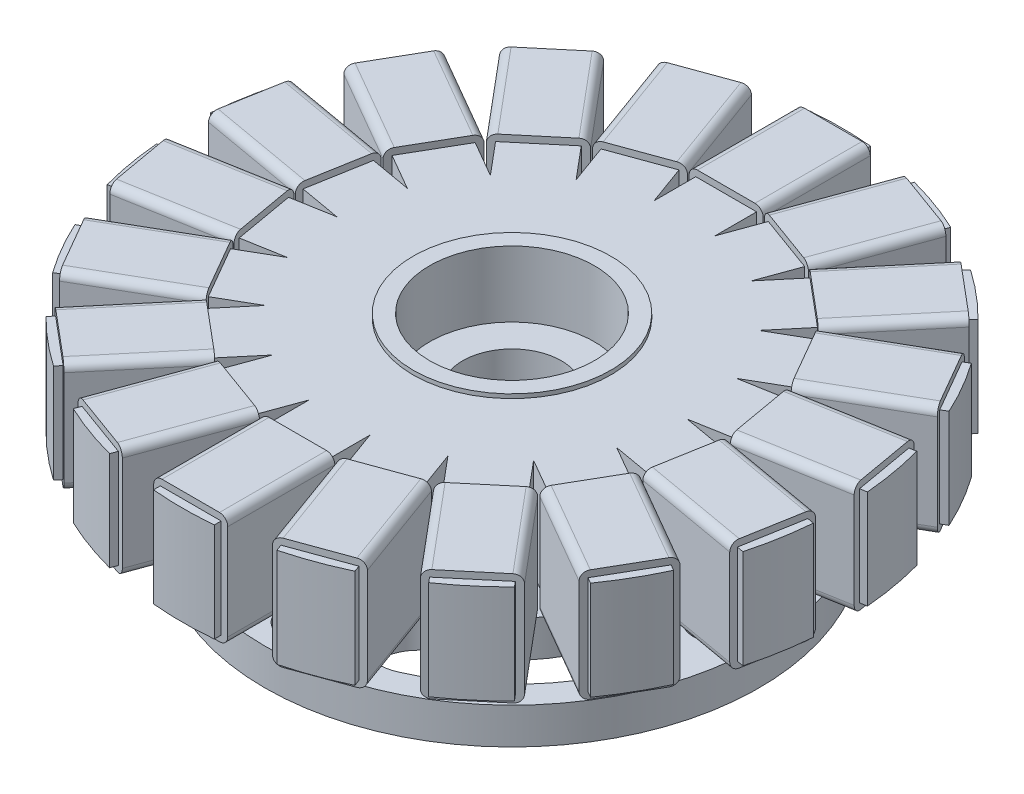
SolidWorks part; units mm, degrees
material "Stainless Steel (ferritic)"
ref_plane "Front Plane" through (0, 0, 0) normal (0, 0, 1) x (1, 0, 0)
ref_plane "Top Plane" through (0, 0, 0) normal (0, 1, 0) x (1, 0, 0)
ref_plane "Right Plane" through (0, 0, 0) normal (1, 0, 0) x (0, 0, -1)
sketch "Sketch1" plane through (0, 0, 0) normal (0, 1, 0) x (1, 0, 0)
  circle A0 centre (0, 0) radius 15
  circle A1 centre (0, 0) radius 12.5 construction
  circle A2 centre (0, 12.5) radius 1.5
  circle A3 centre (12.5, 0) radius 1.5
  circle A4 centre (0, -12.5) radius 1.5
  circle A5 centre (-12.5, 0) radius 1.5
  point P15 (0, 0)
  dimension "D1" = 30
  dimension "D2" = 25
  dimension "D3" = 3
  dimension "D4" = 4
extrude "Boss-Extrude1" add sketch "Sketch1" along normal blind 2.2
sketch "Sketch2" plane through (0, 2.2, 0) normal (0, 1, 0) x (1, 0, 0)
  circle A0 centre (0, 0) radius 6
  dimension "D1" = 12
extrude "Boss-Extrude2" add sketch "Sketch2" along normal blind 10
sketch "Sketch3" plane through (0, 0, 0) normal (0, -1, 0) x (1, 0, 0)
  circle A0 centre (0, 0) radius 5
  dimension "D1" = 10
extrude "Cut-Extrude1" cut sketch "Sketch3" against normal blind 4 contours A0
sketch "Sketch4" plane through (0, 12.2, 0) normal (0, 1, 0) x (1, 0, 0)
  circle A0 centre (0, 0) radius 5
  dimension "D1" = 10
extrude "Cut-Extrude2" cut sketch "Sketch4" against normal blind 4
sketch "Sketch5" plane through (0, 8.2, 0) normal (0, 1, 0) x (1, 0, 0)
  circle A0 centre (0, 0) radius 3
  dimension "D1" = 6
extrude "Cut-Extrude3" cut sketch "Sketch5" against normal blind 10
sketch "Sketch6" plane through (0, 0, 0) normal (0, -1, 0) x (1, 0, 0)
  line L0 (-4.4173, 10.0741) -> (-10.0741, 4.4173) construction
  line L1 (-10.0741, 4.4173) -> (-5.6195, 4.4173) construction
  circle A0 centre (0, 0) radius 11 construction
  arc A1 (-4.4173, 10.0741) -> (-10.0741, 4.4173) centre (0, 0) ccw construction
  arc A2 (-5.4008, 12.3172) -> (-12.3172, 5.4008) centre (0, 0) ccw
  arc A3 (-3.4337, 7.831) -> (-7.831, 3.4337) centre (0, 0) ccw
  arc A4 (-3.4337, 7.831) -> (-5.4008, 12.3172) centre (-4.4173, 10.0741) ccw
  arc A5 (-12.3172, 5.4008) -> (-7.831, 3.4337) centre (-10.0741, 4.4173) ccw
  point P7 (-7.7782, 7.7782)
  dimension "D3" = 22
  dimension "D1" = 45
  dimension "D2" = 8
extrude "Cut-Extrude4" cut sketch "Sketch6" against normal blind 2.2
pattern_circular "CirPattern1" count 4 over 360 about axis through (0, 0, 0) along (0, 1, 0) of "Cut-Extrude4"
ref_plane "Plane1" through (0, 11.95, 0) normal (0, 1, 0) x (1, 0, 0)
sketch "Sketch7" plane through (0, 11.95, 0) normal (0, 1, 0) x (1, 0, 0)
  line L2 (0, 0) -> (-19.6962, -3.473) construction
  line L3 (-19.2915, -5.2763) -> (-9.991, -3.6364)
  line L4 (-19.9327, -1.6399) -> (-10.6322, 0)
  line L5 (-10.6322, 0) -> (-20, 0) construction
  line L6 (-9.991, -3.6364) -> (-18.7939, -6.8404) construction
  line L7 (-6, 0) -> (-10.6322, 0)
  line L8 (-5.6382, -2.0521) -> (-9.991, -3.6364)
  circle A0 centre (0, 0) radius 20 construction
  arc A1 (-19.9327, -1.6399) -> (-19.2915, -5.2763) centre (0, 0) ccw
  circle A2 centre (0, 0) radius 6 construction
  circle A3 centre (0, 0) radius 6
  arc A4 (-6, 0) -> (-5.6382, -2.0521) centre (0, 0) ccw
  dimension "D1" = 40
extrude "Boss-Extrude3" add sketch "Sketch7" against normal blind 6 contours L4 L7 A4 L8 L3 A1
pattern_circular "CirPattern2" count 18 over 360 about axis through (0, 0, 0) along (0, 1, 0) of "Boss-Extrude3"
ref_plane "Plane2" through (0, 0, 13) normal (0, 0, 1) x (1, 0, 0)
sketch "Sketch9" plane through (0, 0, 13) normal (0, 0, 1) x (1, 0, 0)
  line L0 (1.8463, 5.95) -> (1.8463, 11.95) construction
  line L1 (-1.8463, 5.95) -> (1.8463, 5.95) construction
  line L2 (-1.8463, 5.95) -> (-1.8463, 11.95) construction
  line L3 (1.8463, 11.95) -> (-1.8463, 11.95) construction
  line L4 (1.8463, 5.95) -> (1.8463, 11.95)
  line L5 (-1.8463, 5.95) -> (1.8463, 5.95)
  line L6 (-1.8463, 5.95) -> (-1.8463, 11.95)
  line L7 (1.8463, 11.95) -> (-1.8463, 11.95)
  line L9 (-2.2463, 12.35) -> (2.2463, 12.35)
  line L10 (-2.2463, 12.35) -> (-2.2463, 5.55)
  line L11 (-2.2463, 5.55) -> (2.2463, 5.55)
  line L12 (2.2463, 12.35) -> (2.2463, 5.55)
  dimension "D1" = 0.4
  dimension "D2" = 0.4
  dimension "D3" = 0.4
  dimension "D4" = 0.4
extrude "Boss-Extrude4" add sketch "Sketch9" along normal blind 6.5
fillet "Fillet1" radius 0.5 4 edges at (2.2463, 5.55, 16.25) (-2.2463, 5.55, 16.25) (-2.2463, 12.35, 16.25) (2.2463, 12.35, 16.25)
pattern_circular "CirPattern5" count 18 over 360 about axis through (0, 0, 0) along (0, 1, 0) of "Boss-Extrude4", "Fillet1"
